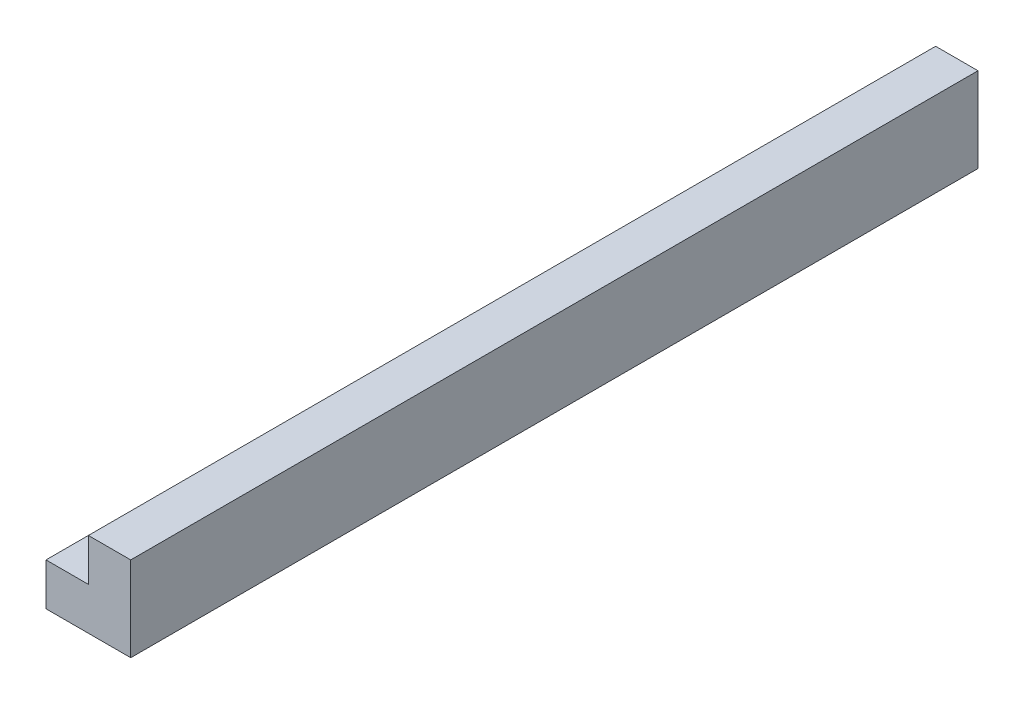
SolidWorks part; units mm, degrees
ref_plane "Plan de face" through (0, 0, 0) normal (0, 0, 1) x (1, 0, 0)
ref_plane "Plan de dessus" through (0, 0, 0) normal (0, 1, 0) x (1, 0, 0)
ref_plane "Plan de droite" through (0, 0, 0) normal (1, 0, 0) x (0, 0, -1)
sketch "Esquisse1" plane through (0, 0, 0) normal (0, 0, 1) x (1, 0, 0)
  line L0 (0, 0) -> (20, 0)
  line L1 (0, 0) -> (20, 0) construction
  line L2 (0, 0) -> (0, 20) construction
  line L3 (0, 20) -> (20, 20) construction
  line L4 (20, 0) -> (20, 20) construction
  line L5 (20, 0) -> (20, 20)
  line L6 (20, 20) -> (10, 20)
  line L7 (10, 20) -> (10, 10)
  line L8 (10, 10) -> (0, 10)
  line L9 (0, 10) -> (0, 0)
  dimension "D2" = 20
extrude "Boss.-Extru.1" add sketch "Esquisse1" along normal blind 200
equation "\"Largeur\"= 20"
equation "\"Longueur\"= 200"
equation "\"Hauteur\"= 20"
equation "\"D1@Esquisse1\"=\"Largeur\""
equation "\"D2@Esquisse1\"=\"Hauteur\""
equation "\"D1@Boss.-Extru.1\"=\"Longueur\""
